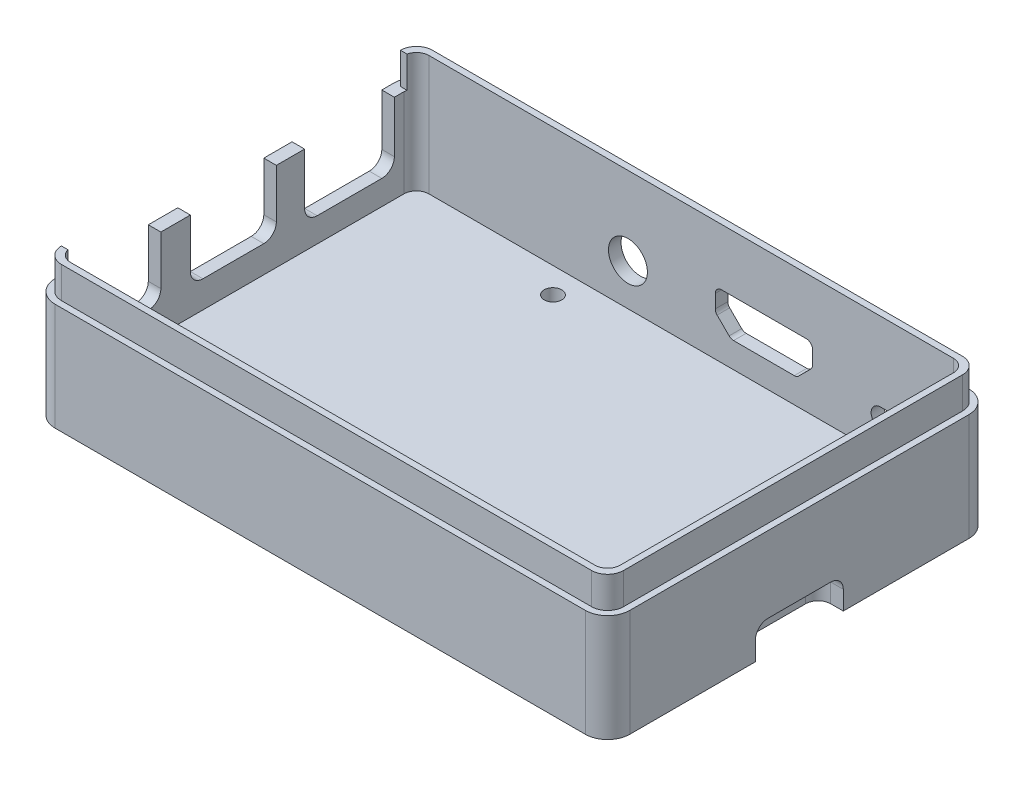
SolidWorks part; units mm, degrees
material "Custom Plastic"
ref_plane "Спереди" through (0, 0, 0) normal (0, 0, 1) x (1, 0, 0)
ref_plane "Сверху" through (0, 0, 0) normal (0, 1, 0) x (1, 0, 0)
ref_plane "Справа" through (0, 0, 0) normal (1, 0, 0) x (0, 0, -1)
ref_plane "Plane1" through (0, 0, 63.69) normal (0, 0, 1) x (1, 0, 0)
sketch "Sketch1" plane through (0, 0, 63.69) normal (0, 0, 1) x (1, 0, 0)
  line L0 (42.5, 14.1) -> (-44.05, 14.1)
  line L1 (-44.05, 14.1) -> (-44.05, -3)
  line L2 (-44.05, -3) -> (42.5, -3)
  line L3 (42.5, -3) -> (42.5, 14.1)
extrude "Boss-Extrude1" add sketch "Sketch1" against normal blind 14
sketch "Sketch2" plane through (0, 0, 49.69) normal (0, 0, -1) x (-1, 0, 0)
  line L0 (-44.5, 14.1) -> (44.05, 14.1)
  line L1 (44.05, 14.1) -> (44.05, -3)
  line L2 (44.05, -3) -> (-44.5, -3)
  line L3 (-44.5, -3) -> (-44.5, 14.1)
extrude "Boss-Extrude2" add sketch "Sketch2" along normal blind 23.55
sketch "Sketch3" plane through (44.5, 0, 0) normal (1, 0, 0) x (0, 0, -1)
  line L0 (-63.69, 14.1) -> (-26.14, 14.1)
  line L1 (-26.14, 14.1) -> (-26.14, -3)
  line L2 (-26.14, -3) -> (-63.69, -3)
  line L3 (-63.69, -3) -> (-63.69, 14.1)
extrude "Boss-Extrude3" add sketch "Sketch3" along normal blind 2
sketch "Sketch4" plane through (0, 0, 63.69) normal (0, 0, 1) x (1, 0, 0)
  line L0 (-44.05, 14.1) -> (46.5, 14.1)
  line L1 (46.5, 14.1) -> (46.5, -3)
  line L2 (46.5, -3) -> (-44.05, -3)
  line L3 (-44.05, -3) -> (-44.05, 14.1)
extrude "Boss-Extrude4" add sketch "Sketch4" along normal blind 23.55
sketch "Sketch5" plane through (0, -3, 0) normal (0, -1, 0) x (1, 0, 0)
  line L0 (44.5, 63.69) -> (44.5, 49.69)
  line L1 (44.5, 49.69) -> (46.5, 49.69)
  line L2 (46.5, 49.69) -> (46.5, 63.69)
  line L3 (46.5, 63.69) -> (44.5, 63.69)
extrude "Cut-Extrude1" cut sketch "Sketch5" against normal blind 3
sketch "Sketch6" plane through (0, 14.1, 0) normal (0, 1, 0) x (-1, 0, 0)
  line L0 (43.05, 29.69) -> (43.05, 83.69)
  line L1 (43.05, 83.69) -> (-44.5, 83.69)
  line L2 (-44.5, 83.69) -> (-44.5, 63.69)
  line L3 (-44.5, 63.69) -> (-42.5, 63.69)
  line L4 (-42.5, 63.69) -> (-42.5, 49.69)
  line L5 (-42.5, 49.69) -> (-44.5, 49.69)
  line L6 (-44.5, 49.69) -> (-44.5, 29.69)
  line L7 (-44.5, 29.69) -> (43.05, 29.69)
extrude "Cut-Extrude2" cut sketch "Sketch6" against normal blind 14.1
sketch "Sketch7" plane through (0, 0, 0) normal (0, -1, 0) x (1, 0, 0)
  line L0 (44.5, 63.69) -> (44.5, 49.69)
  line L1 (44.5, 49.69) -> (46.5, 49.69)
  line L2 (46.5, 49.69) -> (46.5, 63.69)
  line L3 (46.5, 63.69) -> (44.5, 63.69)
extrude "Cut-Extrude3" cut sketch "Sketch7" against normal blind 2
sketch "Sketch8" plane through (0, 14.1, 0) normal (0, 1, 0) x (-1, 0, 0)
  line L0 (-44.5, 83.69) -> (-44.5, 29.69)
  line L1 (-44.5, 29.69) -> (44.05, 29.69)
  line L2 (41.5, 27.14) -> (-45.5, 27.14)
  line L3 (-45.5, 27.14) -> (-45.5, 86.24)
  line L4 (-45.5, 86.24) -> (41.5, 86.24)
  line L5 (44.05, 83.69) -> (-44.5, 83.69)
  arc A0 (44.05, 29.69) -> (41.5, 27.14) centre (41.5, 29.69) cw
  arc A1 (41.5, 86.24) -> (44.05, 83.69) centre (41.5, 83.69) cw
extrude "Boss-Extrude5" add sketch "Sketch8" along normal blind 5
sketch "Sketch9" plane through (0, 0, 83.69) normal (0, 0, -1) x (-1, 0, 0)
  line L0 (43.05, 19.1) -> (-44.5, 19.1)
  line L1 (-44.5, 19.1) -> (-44.5, 0)
  line L2 (-44.5, 0) -> (43.05, 0)
  line L3 (43.05, 0) -> (43.05, 19.1)
extrude "Cut-Extrude4" cut sketch "Sketch9" against normal blind 1.55
sketch "Sketch10" plane through (-44.05, 0, 0) normal (-1, 0, 0) x (0, 0, 1)
  line L0 (87.24, 14.1) -> (87.24, -3)
  line L1 (87.24, -3) -> (26.14, -3)
  line L2 (26.14, -3) -> (26.14, 14.1)
  line L3 (26.14, 14.1) -> (87.24, 14.1)
extrude "Boss-Extrude6" add sketch "Sketch10" along normal blind 1
ref_plane "Plane2" through (0, 0, 28.14) normal (0, 0, -1) x (-1, 0, 0)
sketch "Sketch11" plane through (0, 0, 28.14) normal (0, 0, -1) x (-1, 0, 0)
  line L0 (-44.5, 0) -> (43.05, 0)
  line L1 (43.05, 0) -> (43.05, 19.1)
  line L2 (43.05, 19.1) -> (-44.5, 19.1)
  line L3 (-44.5, 19.1) -> (-44.5, 0)
extrude "Cut-Extrude5" cut sketch "Sketch11" against normal up to next
sketch "Sketch12" plane through (-43.05, 0, 0) normal (1, 0, 0) x (0, 0, -1)
  line L0 (-68.8557, 14.1) -> (-82.5557, 14.1)
  line L1 (-82.5557, 14.1) -> (-82.5557, 4.3)
  line L2 (-82.5557, 4.3) -> (-68.8557, 4.3)
  line L3 (-68.8557, 4.3) -> (-68.8557, 14.1)
extrude "Cut-Extrude6" cut sketch "Sketch12" against normal through all
sketch "Sketch13" plane through (-43.05, 0, 0) normal (1, 0, 0) x (0, 0, -1)
  line L0 (-50.4557, 14.1) -> (-64.1557, 14.1)
  line L1 (-64.1557, 14.1) -> (-64.1557, 4.3)
  line L2 (-64.1557, 4.3) -> (-50.4557, 4.3)
  line L3 (-50.4557, 4.3) -> (-50.4557, 14.1)
extrude "Cut-Extrude7" cut sketch "Sketch13" against normal through all
sketch "Sketch14" plane through (-43.05, 0, 0) normal (1, 0, 0) x (0, 0, -1)
  line L0 (-31.6547, 14.1) -> (-45.9547, 14.1)
  line L1 (-45.9547, 14.1) -> (-45.9547, 3.9)
  line L2 (-45.9547, 3.9) -> (-31.6547, 3.9)
  line L3 (-31.6547, 3.9) -> (-31.6547, 14.1)
extrude "Cut-Extrude8" cut sketch "Sketch14" against normal through all
sketch "Sketch16" plane through (0, 0, 28.14) normal (0, 0, 1) x (1, 0, 0)
  line L0 (20.0578, 10.08) -> (4.5578, 10.08)
  line L1 (4.5578, 10.08) -> (4.5578, 6.53)
  line L2 (4.5578, 6.53) -> (7.0578, 4.03)
  line L3 (7.0578, 4.03) -> (17.5578, 4.03)
  line L4 (17.5578, 4.03) -> (20.0578, 6.53)
  line L5 (20.0578, 6.53) -> (20.0578, 10.08)
extrude "Cut-Extrude10" cut sketch "Sketch16" against normal through all
sketch "Sketch17" plane through (0, 0, 26.14) normal (0, 0, -1) x (-1, 0, 0)
  line L0 (-36.3834, 5.068) -> (-30.8834, 5.068) construction
  line L1 (-36.3834, 6.568) -> (-30.8834, 6.568)
  line L2 (-36.3834, 3.568) -> (-30.8834, 3.568)
  arc A0 (-36.3834, 6.568) -> (-36.3834, 3.568) centre (-36.3834, 5.068) ccw
  arc A1 (-30.8834, 3.568) -> (-30.8834, 6.568) centre (-30.8834, 5.068) ccw
  point P2 (-33.6334, 5.068)
  point P11 (-36.3834, 5.068)
  point P12 (-30.8834, 5.068)
  dimension "D1" = 3
  dimension "D2" = 5.5
extrude "Cut-Extrude11" cut sketch "Sketch17" against normal up to next
hole_wizard "Ø2.8 (2.8) Diameter Hole1" positions "Sketch19" profile "Sketch18" hole size "Ø2.8" standard "ISO" end condition through all
sketch "Sketch19" plane through (0, 0, 0) normal (0, 1, 0) x (1, 0, 0)
  point P0 (40.75, -81.19)
  point P1 (40.75, -32.19)
  point P2 (-17.25, -32.19)
  point P3 (-17.25, -81.19)
sketch "Sketch18" plane through (40.75, 0, 81.19) normal (1, 0, 0) x (0, 0, 1)
  line L0 (0, 0) -> (0, 3)
  line L1 (0, 3) -> (1.4, 3)
  line L2 (1.4, 3) -> (1.4, 0)
  line L5 (1.4, 0) -> (0, 0)
  line L11 (0, -6.35) -> (0, 107.95) construction
  dimension "Thru Hole Dia." = 2.8
  dimension "Thru Hole Depth" = 3
hole_wizard "Ø6.2 (6.2) Diameter Hole1" positions "Sketch21" profile "Sketch20" hole size "Ø6.2" standard "ANSI Metric"
sketch "Sketch21" plane through (0, 0, 26.14) normal (0, 0, -1) x (-1, 0, 0)
  point P0 (9.3535, 6.6)
sketch "Sketch20" plane through (-9.3535, 6.6, 26.14) normal (1, 0, 0) x (0, 1, 0)
  line L0 (0, 0) -> (0, 2)
  line L1 (0, 2) -> (3.1, 2)
  line L2 (3.1, 2) -> (3.1, 0)
  line L5 (3.1, 0) -> (0, 0)
  line L11 (0, -6.35) -> (0, 107.95) construction
  dimension "Thru Hole Dia." = 6.2
  dimension "Thru Hole Depth" = 2
fillet "Fillet1" radius 1 6 edges at (7.0578, 4.03, 27.14) (20.0578, 6.53, 27.14) (4.5578, 6.53, 27.14) (4.5578, 10.08, 27.14) (20.0578, 10.08, 27.14) (17.5578, 4.03, 27.14)
fillet "Fillet2" radius 2 14 edges at (42.5, -1.5, 49.69) (42.5, -1.5, 63.69) (-44.05, 4.3, 82.5557) (45.5, 2, 63.69) (-44.05, 4.3, 64.1557) (-43.05, 9.55, 85.24) (44.5, 9.55, 85.24) (-44.05, 4.3, 50.4557) (45.5, 2, 49.69) (-44.05, 3.9, 45.9547) (-44.05, 4.3, 68.8557) (-44.05, 3.9, 31.6547) (44.5, 9.55, 28.14) (-43.05, 9.55, 28.14)
fillet "Fillet3" radius 2.55 2 edges at (45.5, 16.6, 86.24) (45.5, 16.6, 27.14)
fillet "Fillet4" radius 3.55 4 edges at (46.5, 5.55, 87.24) (-45.05, 5.55, 87.24) (46.5, 5.55, 26.14) (-45.05, 5.55, 26.14)
